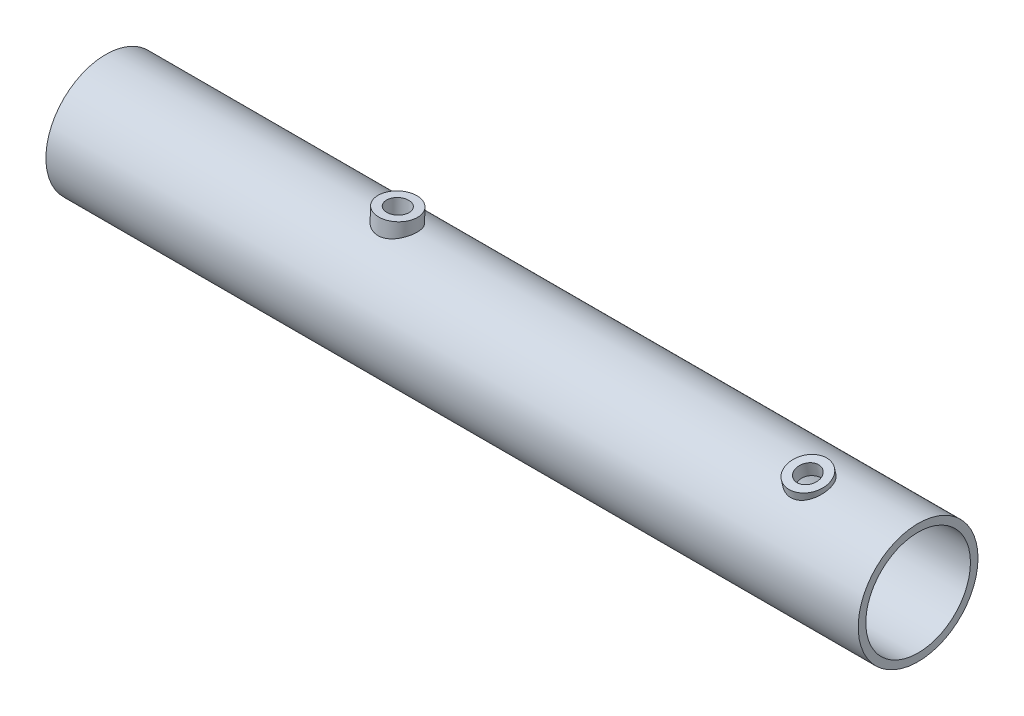
SolidWorks part; units mm, degrees
material "201 Tavlı Paslanmaz Çelik (SS)"
ref_plane "Ön Düzlem" through (0, 0, 0) normal (0, 0, 1) x (1, 0, 0)
ref_plane "Üst Düzlem" through (0, 0, 0) normal (0, 1, 0) x (1, 0, 0)
ref_plane "Sağ Düzlem" through (0, 0, 0) normal (1, 0, 0) x (0, 0, -1)
sketch "Çizim1" plane through (0, 0, 0) normal (1, 0, 0) x (0, 0, -1)
  circle A0 centre (0, 0) radius 19
  circle A1 centre (0, 0) radius 21.75
extrude "Yükseklik-Ekstrüzyon1" add sketch "Çizim1" along normal blind 295
sketch "Çizim3" plane through (295, 0, 0) normal (1, 0, 0) x (0, 0, -1)
  circle A0 centre (0, 0) radius 19 construction
  circle A1 centre (0, 0) radius 19
sketch "Çizim4" plane through (0, 0, 0) normal (0, 0, 1) x (1, 0, 0)
  line L0 (295, 0) -> (0, 0) construction
sketch "Çizim5" plane through (0.0226, 23.1666, 5.2641) normal (-0.001, -0.9751, -0.2216) x (1, -0.0009, -0.0002)
  circle A0 centre (260.4367, 0.2915) radius 4 construction
  circle A1 centre (260.4367, 0.2915) radius 7
  circle A2 centre (260.4367, 0.2915) radius 7
  circle A3 centre (260.4367, 0.2915) radius 4
  dimension "D1" = 0
extrude "Yükseklik-Ekstrüzyon2" add sketch "Çizim5" along normal up to surface (2.0778 mm away)
sketch "Çizim6" plane through (0.1921, 27.1573, -0.6821) normal (-0.0071, -0.9997, 0.0251) x (1, -0.0071, 0.0002)
  circle A0 centre (105.2784, 0.0875) radius 4 construction
  circle A1 centre (105.2784, 0.0875) radius 7
  circle A2 centre (105.2784, 0.0875) radius 7
  circle A3 centre (105.2784, 0.0875) radius 4
  dimension "D1" = 0
extrude "Yükseklik-Ekstrüzyon3" add sketch "Çizim6" along normal up to surface (5.0265 mm away)
sketch "Çizim7" plane through (0.0226, 23.1666, 5.2641) normal (0.001, 0.9751, 0.2216) x (1, -0.0009, -0.0002)
  circle A0 centre (260.4367, -0.2915) radius 4 construction
  circle A1 centre (260.4367, -0.2915) radius 4
extrude "Kes-Ekstrüzyon1" cut sketch "Çizim7" against normal blind 10
sketch "Çizim8" plane through (0.1921, 27.1573, -0.6821) normal (0.0071, 0.9997, -0.0251) x (1, -0.0071, 0.0002)
  circle A0 centre (105.2784, -0.0875) radius 4 construction
  circle A1 centre (105.2784, -0.0875) radius 4
extrude "Kes-Ekstrüzyon2" cut sketch "Çizim8" against normal blind 20
